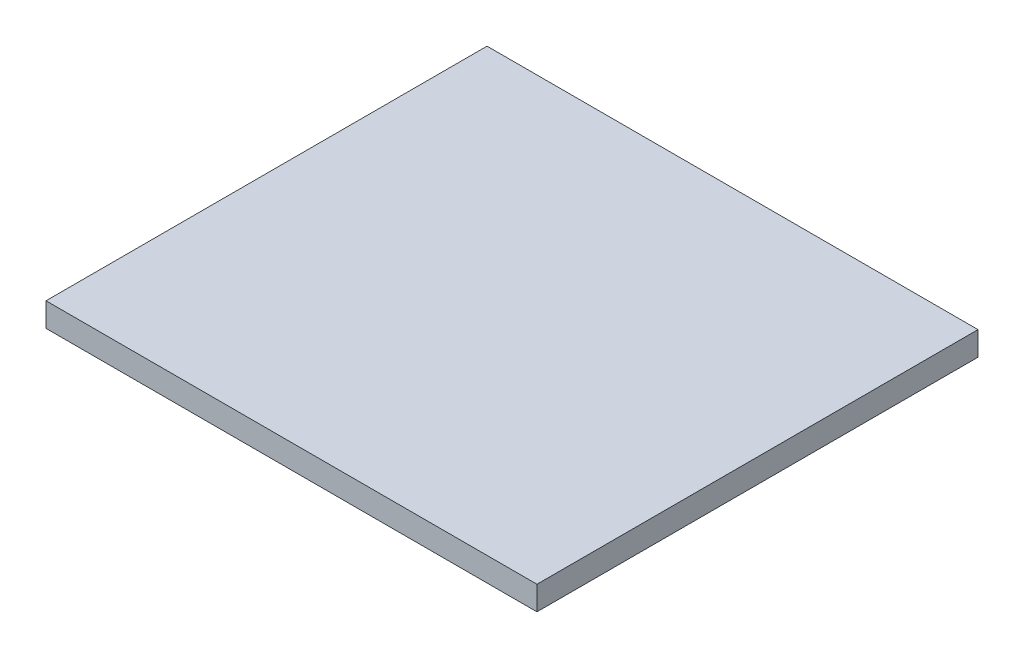
SolidWorks part; units mm, degrees
material "Pine"
ref_plane "Front Plane" through (0, 0, 0) normal (0, 0, 1) x (1, 0, 0)
ref_plane "Top Plane" through (0, 0, 0) normal (0, 1, 0) x (1, 0, 0)
ref_plane "Right Plane" through (0, 0, 0) normal (1, 0, 0) x (0, 0, -1)
sketch "Sketch1" plane through (0, 0, 0) normal (0, 1, 0) x (1, 0, 0)
  line L1 (-187.325, 336.55) -> (187.325, 336.55)
  line L2 (-187.325, 336.55) -> (-187.325, 0)
  line L3 (-187.325, 0) -> (187.325, 0)
  line L4 (187.325, 336.55) -> (187.325, 0)
  point P4 (0, 0)
  dimension "D1" = 374.65
  dimension "D2" = 336.55
extrude "Boss-Extrude1" add sketch "Sketch1" along normal blind 18.2562
